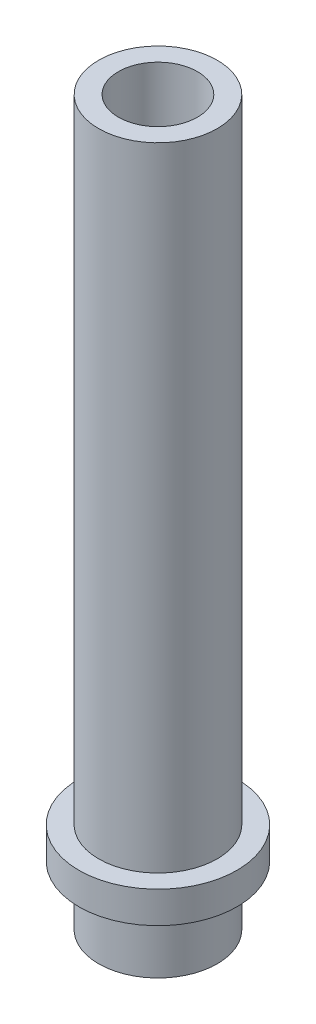
SolidWorks part; units mm, degrees
ref_plane "Front Plane" through (0, 0, 0) normal (0, 0, 1) x (1, 0, 0)
ref_plane "Top Plane" through (0, 0, 0) normal (0, 1, 0) x (1, 0, 0)
ref_plane "Right Plane" through (0, 0, 0) normal (1, 0, 0) x (0, 0, -1)
sketch "Sketch1" plane through (0, 0, 0) normal (0, 1, 0) x (1, 0, 0)
  circle A0 centre (0, 0) radius 6.35
  dimension "D1" = 12.7
extrude "Boss-Extrude1" add sketch "Sketch1" along normal blind 2.54
sketch "Sketch2" plane through (0, 0, 0) normal (0, -1, 0) x (1, 0, 0)
  circle A0 centre (0, 0) radius 4.7625
  dimension "D1" = 9.525
extrude "Boss-Extrude2" add sketch "Sketch2" along normal blind 4.7625
sketch "Sketch3" plane through (0, 2.54, 0) normal (0, 1, 0) x (1, 0, 0)
  circle A0 centre (0, 0) radius 4.7625
  dimension "D1" = 9.525
extrude "Boss-Extrude3" add sketch "Sketch3" along normal blind 50.8
sketch "Sketch4" plane through (0, 53.34, 0) normal (0, 1, 0) x (1, 0, 0)
  circle A0 centre (0, 0) radius 3.175
  point P2 (-1.9551, -1.7603)
  point P3 (0, 0)
  dimension "D1" = 6.35
extrude "Cut-Extrude1" cut sketch "Sketch4" against normal blind 25.4
